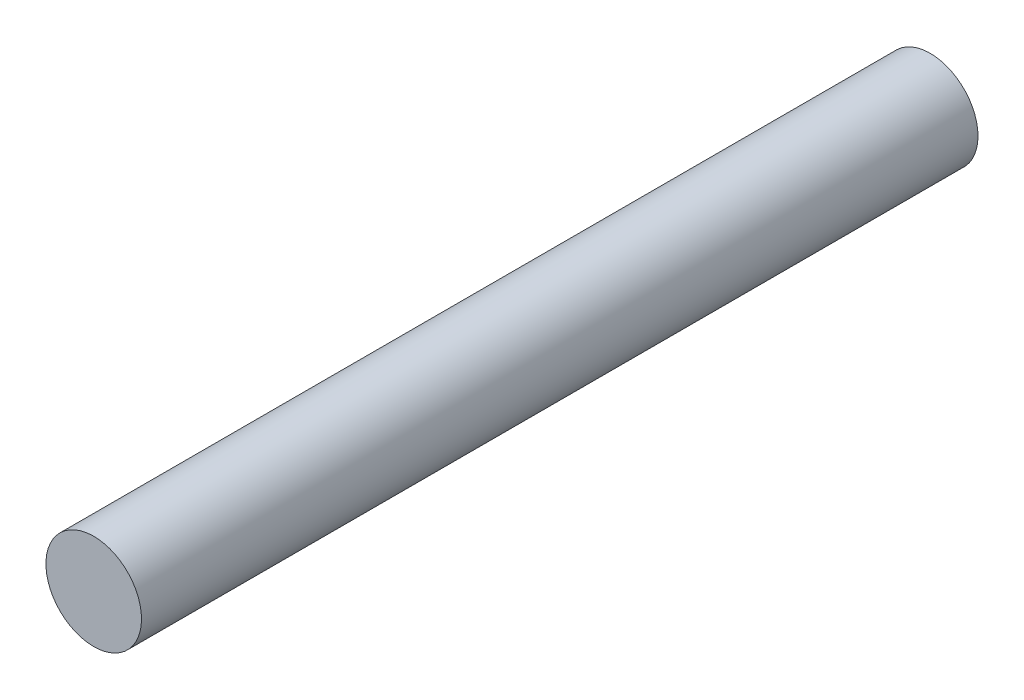
SolidWorks part; units mm, degrees
ref_plane "前视基准面" through (0, 0, 0) normal (0, 0, 1) x (1, 0, 0)
ref_plane "上视基准面" through (0, 0, 0) normal (0, 1, 0) x (1, 0, 0)
ref_plane "右视基准面" through (0, 0, 0) normal (1, 0, 0) x (0, 0, -1)
sketch "草图1" plane through (0, 0, 0) normal (0, 0, 1) x (1, 0, 0)
  circle A0 centre (0, 0) radius 4
extrude "凸台-拉伸1" add sketch "草图1" along normal blind 70
